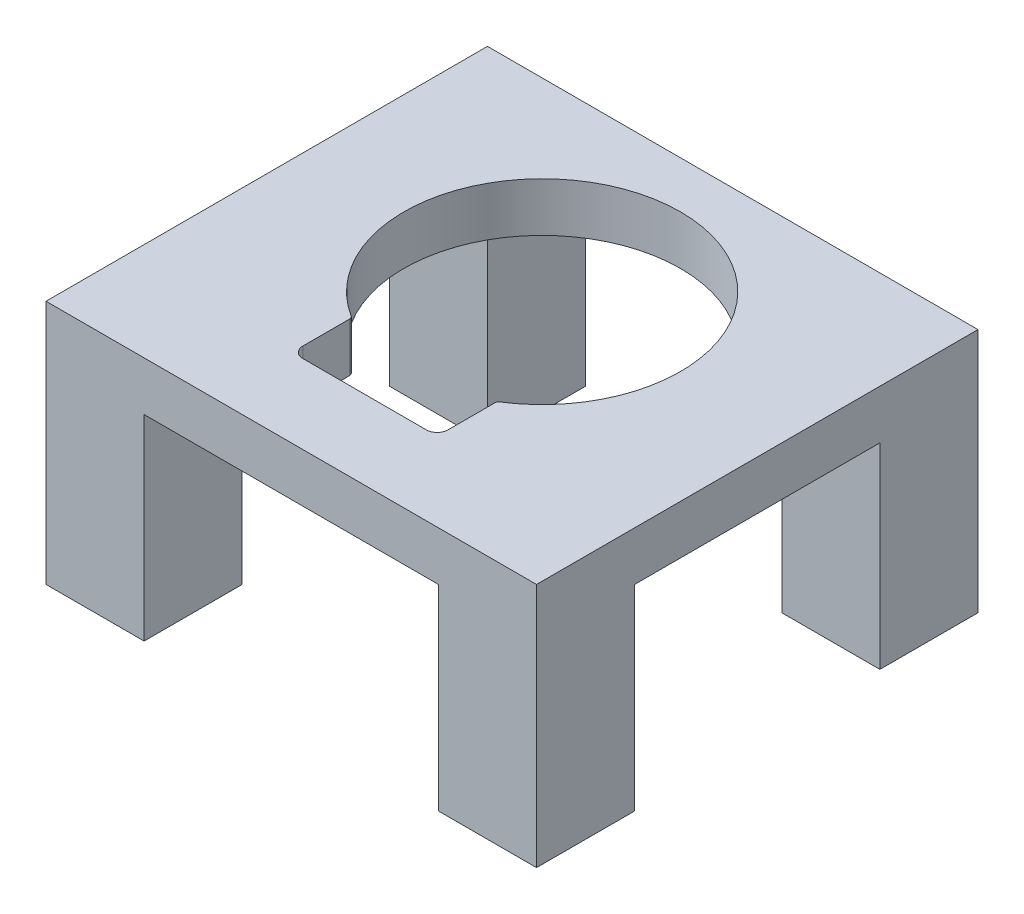
SolidWorks part; units mm, degrees
ref_plane "Front Plane" through (0, 0, 0) normal (0, 0, 1) x (1, 0, 0)
ref_plane "Top Plane" through (0, 0, 0) normal (0, 1, 0) x (1, 0, 0)
ref_plane "Right Plane" through (0, 0, 0) normal (1, 0, 0) x (0, 0, -1)
sketch "Sketch1" plane through (0, 0, 0) normal (0, 1, 0) x (1, 0, 0)
  line L3 (-7.4, -15) -> (-7.4, -10.2233)
  line L4 (7.4, -10.2233) -> (7.4, -15)
  line L5 (6.3, -16.1) -> (-6.3, -16.1)
  line L7 (-24.4433, 20.8692) -> (25.5567, 20.8692)
  line L8 (-24.4433, 20.8692) -> (-24.4433, -24.1308)
  line L9 (-24.4433, -24.1308) -> (25.5567, -24.1308)
  line L10 (25.5567, 20.8692) -> (25.5567, -24.1308)
  arc A5 (-7.4, -10.2233) -> (-7.5848, -9.8861) centre (-7.8, -10.2233) ccw
  arc A6 (7.5848, -9.8861) -> (-7.5848, -9.8861) centre (0, 2) ccw
  arc A7 (7.5848, -9.8861) -> (7.4, -10.2233) centre (7.8, -10.2233) ccw
  arc A8 (6.3, -16.1) -> (7.4, -15) centre (6.3, -15) ccw
  arc A9 (-7.4, -15) -> (-6.3, -16.1) centre (-6.3, -15) ccw
  dimension "D1" = 14.1
  dimension "D2" = 0.4
  dimension "D4" = 1.1
  dimension "D6" = 1.1
  dimension "D8" = 0.4
  dimension "D9" = 50
  dimension "D3" = 4.7767
  dimension "D5" = 12.6
  dimension "D7" = 4.7767
  dimension "D10" = 45
extrude "Boss-Extrude1" add sketch "Sketch1" along normal blind 5
sketch "Sketch2" plane through (0, 0, 0) normal (0, -1, 0) x (1, 0, 0)
  line L0 (0.5567, 24.1308) -> (0.5567, -20.8692) construction
  line L1 (-24.4433, 24.1308) -> (-14.4433, 24.1308)
  line L2 (-24.4433, 24.1308) -> (-24.4433, 14.1308)
  line L3 (-24.4433, 14.1308) -> (-14.4433, 14.1308)
  line L4 (-14.4433, 24.1308) -> (-14.4433, 14.1308)
  line L5 (-24.4433, 24.1308) -> (25.5567, 24.1308) construction
  line L6 (25.5567, -20.8692) -> (-24.4433, -20.8692) construction
  line L7 (-24.4433, 1.6308) -> (25.5567, 1.6308) construction
  line L8 (-24.4433, -20.8692) -> (-24.4433, 24.1308) construction
  line L9 (25.5567, 24.1308) -> (25.5567, -20.8692) construction
  line L10 (-14.4433, -20.8692) -> (-14.4433, -10.8692)
  line L11 (-24.4433, -10.8692) -> (-14.4433, -10.8692)
  line L12 (-24.4433, -20.8692) -> (-24.4433, -10.8692)
  line L13 (-24.4433, -20.8692) -> (-14.4433, -20.8692)
  line L14 (25.5567, -20.8692) -> (15.5567, -20.8692)
  line L15 (25.5567, -20.8692) -> (25.5567, -10.8692)
  line L16 (25.5567, -10.8692) -> (15.5567, -10.8692)
  line L17 (15.5567, -20.8692) -> (15.5567, -10.8692)
  line L18 (15.5567, 24.1308) -> (15.5567, 14.1308)
  line L19 (25.5567, 14.1308) -> (15.5567, 14.1308)
  line L20 (25.5567, 24.1308) -> (25.5567, 14.1308)
  line L21 (25.5567, 24.1308) -> (15.5567, 24.1308)
  dimension "D1" = 10
  dimension "D2" = 10
extrude "Boss-Extrude2" add sketch "Sketch2" along normal blind 20
